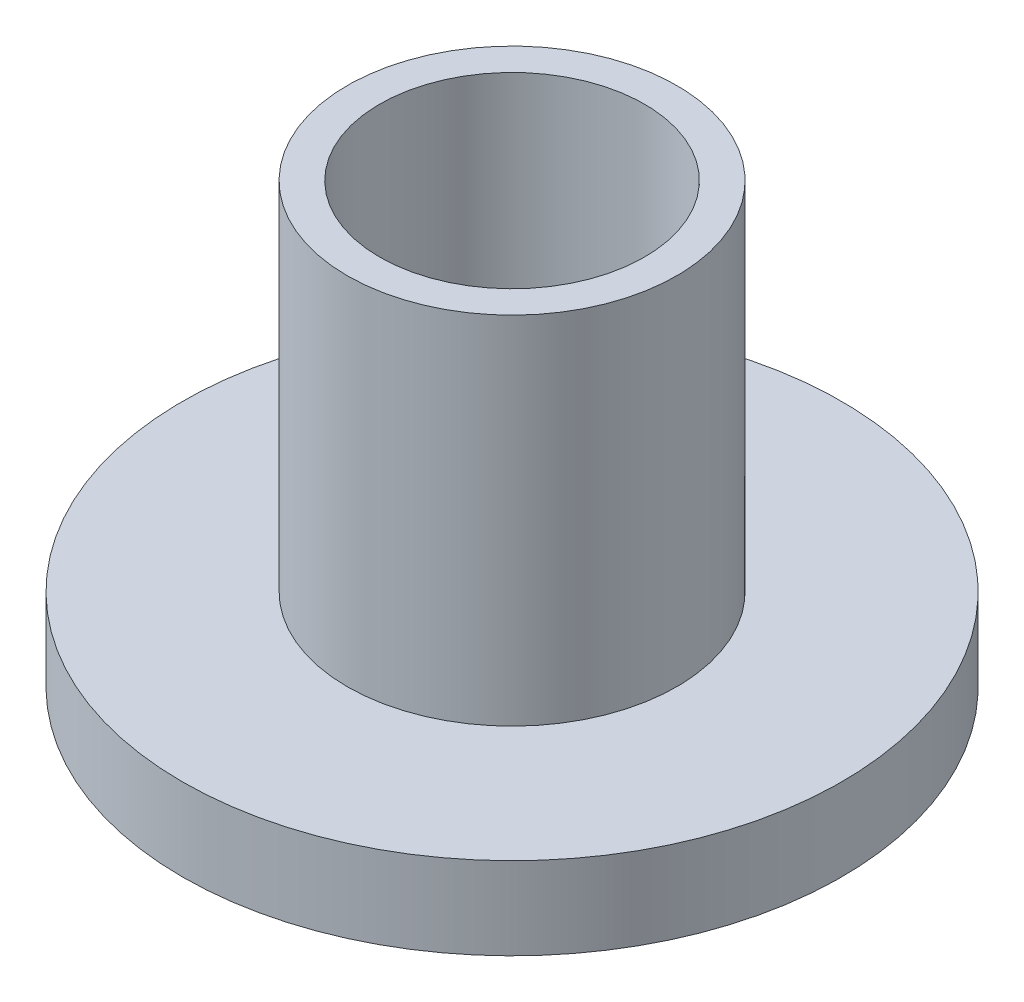
SolidWorks part; units mm, degrees
material "PET"
ref_plane "Front Plane" through (0, 0, 0) normal (0, 0, 1) x (1, 0, 0)
ref_plane "Top Plane" through (0, 0, 0) normal (0, 1, 0) x (1, 0, 0)
ref_plane "Right Plane" through (0, 0, 0) normal (1, 0, 0) x (0, 0, -1)
sketch "Sketch1" plane through (0, 0, 0) normal (0, 1, 0) x (1, 0, 0)
  circle A0 centre (0, 0) radius 6.35
  dimension "D1" = 12.7
extrude "Boss-Extrude1" add sketch "Sketch1" along normal blind 1.5875
sketch "Sketch2" plane through (0, 1.5875, 0) normal (0, 1, 0) x (1, 0, 0)
  circle A0 centre (0, 0) radius 3.175
  dimension "D1" = 6.35
extrude "Boss-Extrude2" add sketch "Sketch2" along normal blind 6.858
sketch "Sketch3" plane through (0, 8.4455, 0) normal (0, 1, 0) x (1, 0, 0)
  circle A0 centre (0, 0) radius 2.5527
  dimension "D1" = 5.1054
extrude "Cut-Extrude1" cut sketch "Sketch3" against normal through all
